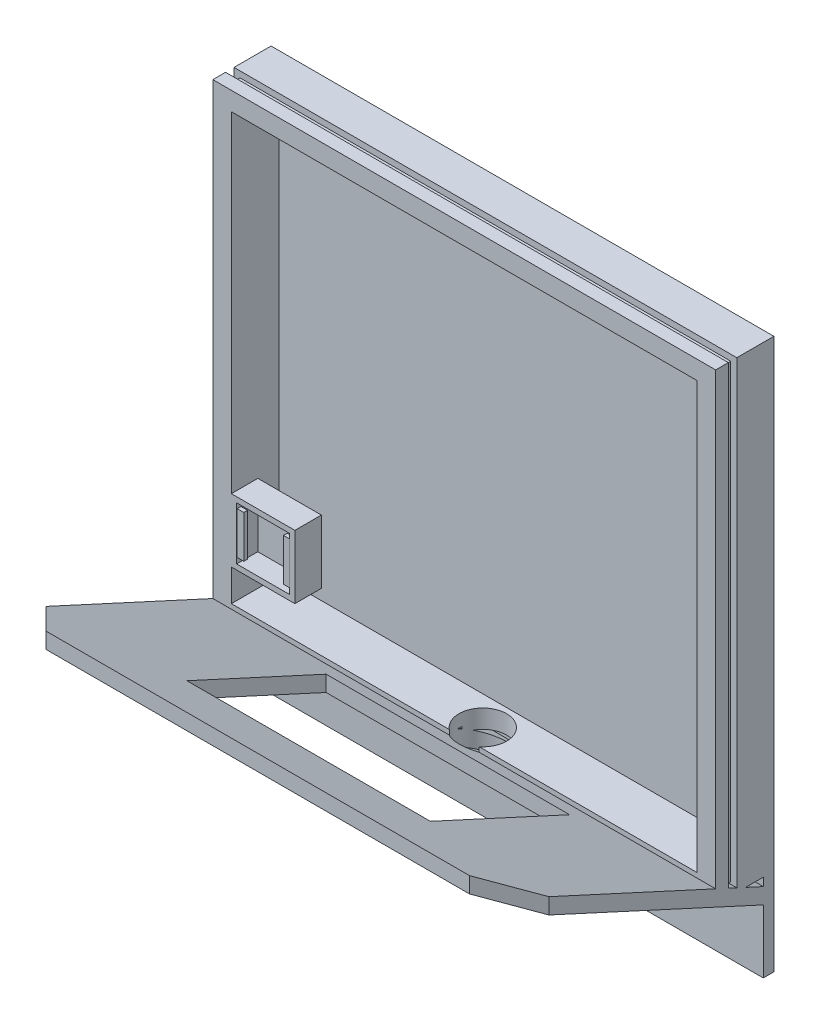
SolidWorks part; units mm, degrees
ref_plane "Front Plane" through (0, 0, 0) normal (0, 0, 1) x (1, 0, 0)
ref_plane "Top Plane" through (0, 0, 0) normal (0, 1, 0) x (1, 0, 0)
ref_plane "Right Plane" through (0, 0, 0) normal (1, 0, 0) x (0, 0, -1)
sketch "190 x 200 Tray Floor Sketch" plane through (0, 0, 0) normal (0, 0, 1) x (1, 0, 0)
  line L1 (-95, -8) -> (95, -8)
  line L2 (-95, -8) -> (-95, 200)
  line L3 (-95, 200) -> (95, 200)
  line L4 (95, -8) -> (95, 200)
extrude "4 mm Tray Floor" add sketch "190 x 200 Tray Floor Sketch" along normal blind 4 separate body
sketch "Electronics Compartment Wall Sketch" plane through (0, 0, 0) normal (0, 0, 1) x (1, 0, 0)
  line L0 (-95, 200) -> (-95, -8) construction
  line L1 (-95, 25) -> (95, 25)
  line L2 (-95, 25) -> (-95, 200)
  line L3 (-95, 200) -> (95, 200)
  line L4 (95, 25) -> (95, 200)
  line L6 (-88, 32) -> (88, 32)
  line L7 (-88, 32) -> (-88, 193)
  line L8 (-88, 193) -> (88, 193)
  line L9 (88, 32) -> (88, 193)
extrude "22 mm Perimeter Walls" add sketch "Electronics Compartment Wall Sketch" along normal blind 22
sketch "External Wall Cord Gasket Groove Sketch" plane through (0, 0, 0) normal (0, 0, 1) x (1, 0, 0)
  line L1 (-96, 24) -> (96, 24)
  line L2 (-96, 24) -> (-96, 201)
  line L3 (-96, 201) -> (96, 201)
  line L4 (96, 24) -> (96, 201)
  line L5 (-92.7, 27.3) -> (92.7, 27.3)
  line L6 (-92.7, 27.3) -> (-92.7, 197.7)
  line L7 (-92.7, 197.7) -> (92.7, 197.7)
  line L8 (92.7, 27.3) -> (92.7, 197.7)
extrude "3.2 High x 2.3 Deep External Perimeter Gasket Groove" cut sketch "External Wall Cord Gasket Groove Sketch" against normal blind 3.2 from offset 17.2
ref_plane "GPS Antenna Shelf Plane" through (0, 0, 12) normal (0, 0, 1) x (1, 0, 0)
sketch "24 mm GPS Antenna Shelf Sketch" plane through (0, 0, 12) normal (0, 0, 1) x (1, 0, 0)
  line L0 (-88, 193) -> (-88, 32) construction
  line L1 (-88, 44) -> (-64, 44)
  line L2 (-88, 44) -> (-88, 68)
  line L3 (-88, 68) -> (-64, 68)
  line L4 (-64, 44) -> (-64, 68)
extrude "2 mm GPS Antenna Shelf" add sketch "24 mm GPS Antenna Shelf Sketch" along normal blind 2
ref_plane "GPS Antenna Guide Plane" through (0, 0, 13.5) normal (0, 0, 1) x (1, 0, 0)
sketch "20 mm GPS Antenna Guide Ring Sketch" plane through (0, 0, 13.5) normal (0, 0, 1) x (1, 0, 0)
  line L0 (-88, 193) -> (-88, 32) construction
  line L1 (-88, 44) -> (-64, 44)
  line L2 (-88, 44) -> (-88, 68)
  line L3 (-88, 68) -> (-64, 68)
  line L4 (-64, 44) -> (-64, 68)
  line L6 (-86, 46) -> (-66, 46)
  line L7 (-86, 46) -> (-86, 66)
  line L8 (-86, 66) -> (-66, 66)
  line L9 (-66, 46) -> (-66, 66)
extrude "8.5 mm GPS Antenna Guide Ring" add sketch "20 mm GPS Antenna Guide Ring Sketch" along normal blind 8.5
ref_plane "GPS Antenna Clip Plane" through (0, 0, 20.4) normal (0, 0, 1) x (1, 0, 0)
sketch "Left GPS Antenna Snap Lip Sketch" plane through (0, 0, 20.4) normal (0, 0, 1) x (1, 0, 0)
  line L0 (-86, 66) -> (-86, 46) construction
  line L1 (-86, 48) -> (-83.5, 48)
  line L2 (-86, 48) -> (-86, 64)
  line L3 (-86, 64) -> (-83.5, 64)
  line L4 (-83.5, 48) -> (-83.5, 64)
extrude "Left GPS Antenna Snap Lip" add sketch "Left GPS Antenna Snap Lip Sketch" along normal blind 1.4
sketch "Right GPS Antenna Snap Lip Sketch" plane through (0, 0, 20.4) normal (0, 0, 1) x (1, 0, 0)
  line L0 (-66, 46) -> (-66, 66) construction
  line L1 (-68.5, 48) -> (-66, 48)
  line L2 (-68.5, 48) -> (-68.5, 64)
  line L3 (-68.5, 64) -> (-66, 64)
  line L4 (-66, 48) -> (-66, 64)
extrude "Right GPS Antenna Snap Lip" add sketch "Right GPS Antenna Snap Lip Sketch" along normal blind 1.4
sketch "Angled Display Bulkhead Side Profile" plane through (0, 0, 0) normal (1, 0, 0) x (0, 0, -1)
  line L0 (-2, 15) -> (-2, 21)
  line L1 (-2, 21) -> (-100, 66)
  line L2 (-100, 66) -> (-100, 60)
  line L3 (-100, 60) -> (-2, 15)
extrude "190 mm Wide Angled Display Bulkhead" add sketch "Angled Display Bulkhead Side Profile" along normal blind 95 and the other way blind 95
sketch "92 x 58 Display Opening Side Profile" plane through (0, 0, 0) normal (1, 0, 0) x (0, 0, -1)
  line L0 (-28.2, 25) -> (-28.2, 35)
  line L1 (-28.2, 35) -> (-80.8, 59.2)
  line L2 (-80.8, 59.2) -> (-80.8, 49.2)
  line L3 (-80.8, 49.2) -> (-28.2, 25)
extrude "92 x 58 mm Display Opening" cut sketch "92 x 58 Display Opening Side Profile" against normal blind 46 and the other way blind 46
sketch "18 mm Front Harness Grommet Sketch" plane through (0, 0, 0) normal (0, 1, 0) x (1, 0, 0)
  circle A0 centre (0, -15) radius 9
extrude "18 mm Front 12 V and Sensor Harness Passage" cut sketch "18 mm Front Harness Grommet Sketch" against normal blind 40 and the other way blind 40
sketch "Left Screen Holder Corner Chamfer Sketch" plane through (0, 0, 0) normal (0, 1, 0) x (1, 0, 0)
  line L0 (-95, -100) -> (-80, -100)
  line L1 (-95, -100) -> (95, -100) construction
  line L2 (-80, -100) -> (-95, -85)
  line L3 (-95, -22) -> (-95, -100) construction
  line L4 (-95, -85) -> (-95, -100)
extrude "Left Screen Holder Corner Chamfer" cut sketch "Left Screen Holder Corner Chamfer Sketch" against normal blind 110 and the other way blind 110
sketch "Right Screen Holder Corner Chamfer Sketch" plane through (0, 0, 0) normal (0, 1, 0) x (1, 0, 0)
  line L0 (95, -100) -> (80, -100)
  line L1 (-80, -100) -> (95, -100) construction
  line L2 (80, -100) -> (95, -85)
  line L3 (95, -22) -> (95, -100) construction
  line L4 (95, -85) -> (95, -100)
extrude "Right Screen Holder Corner Chamfer" cut sketch "Right Screen Holder Corner Chamfer Sketch" against normal blind 110 and the other way blind 110
